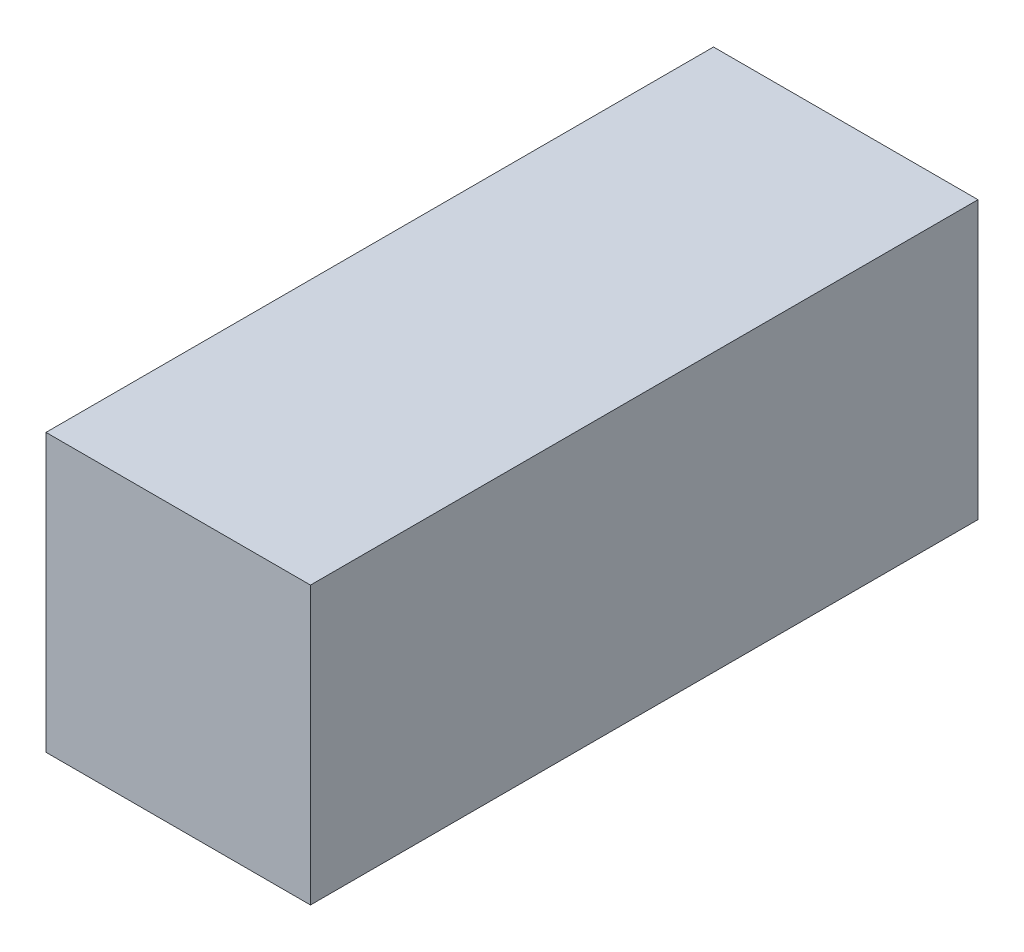
SolidWorks part; units mm, degrees
ref_plane "Front Plane" through (0, 0, 0) normal (0, 0, 1) x (1, 0, 0)
ref_plane "Top Plane" through (0, 0, 0) normal (0, 1, 0) x (1, 0, 0)
ref_plane "Right Plane" through (0, 0, 0) normal (1, 0, 0) x (0, 0, -1)
sketch "Sketch1" plane through (0, 0, 0) normal (0, 1, 0) x (1, 0, 0)
  line L1 (0, 0) -> (21, 0)
  line L2 (0, 0) -> (0, -53)
  line L3 (0, -53) -> (21, -53)
  line L4 (21, 0) -> (21, -53)
  dimension "D1" = 21
  dimension "D2" = 53
extrude "Boss-Extrude1" add sketch "Sketch1" along normal blind 22
